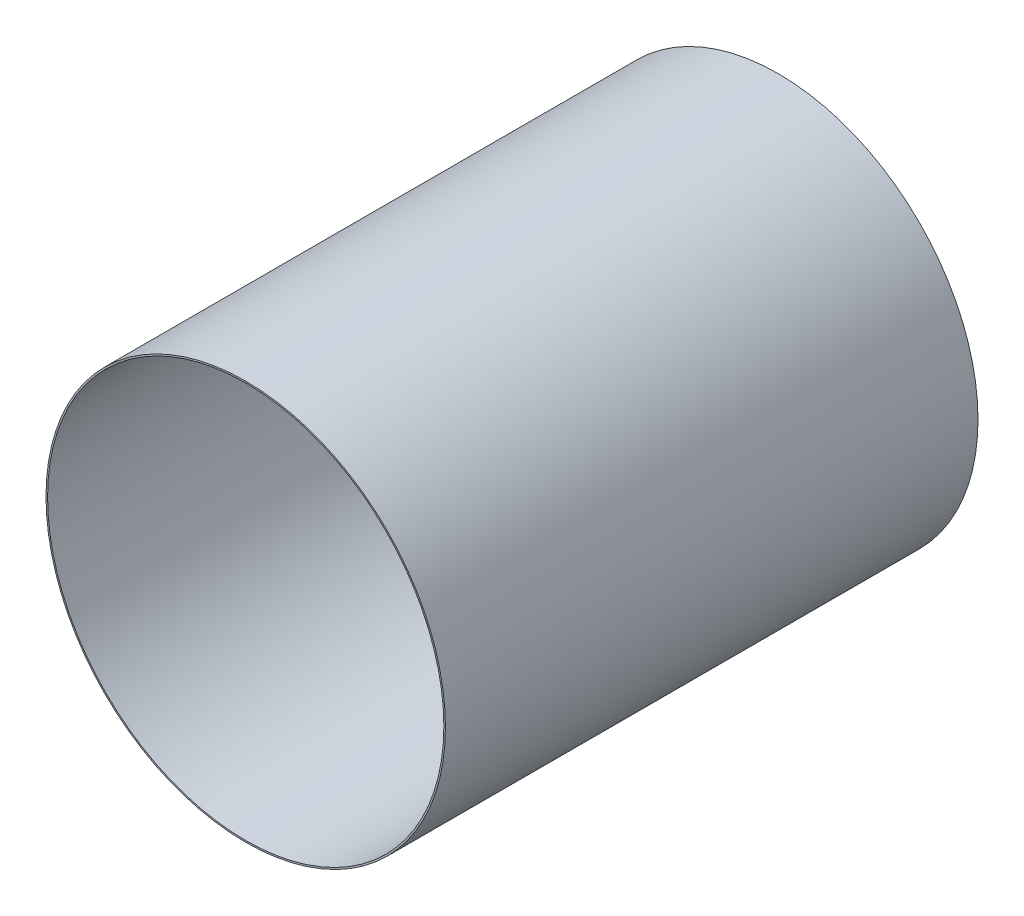
SolidWorks part; units mm, degrees
ref_plane "Front Plane" through (0, 0, 0) normal (0, 0, 1) x (1, 0, 0)
ref_plane "Top Plane" through (0, 0, 0) normal (0, 1, 0) x (1, 0, 0)
ref_plane "Right Plane" through (0, 0, 0) normal (1, 0, 0) x (0, 0, -1)
sketch "Sketch1" plane through (0, 0, 0) normal (0, 0, 1) x (1, 0, 0)
  circle A0 centre (0, 0) radius 38.1
  dimension "D1" = 76.2
extrude "Boss-Extrude1" add sketch "Sketch1" along normal blind 101.6
shell "Shell1" thickness 0.3
